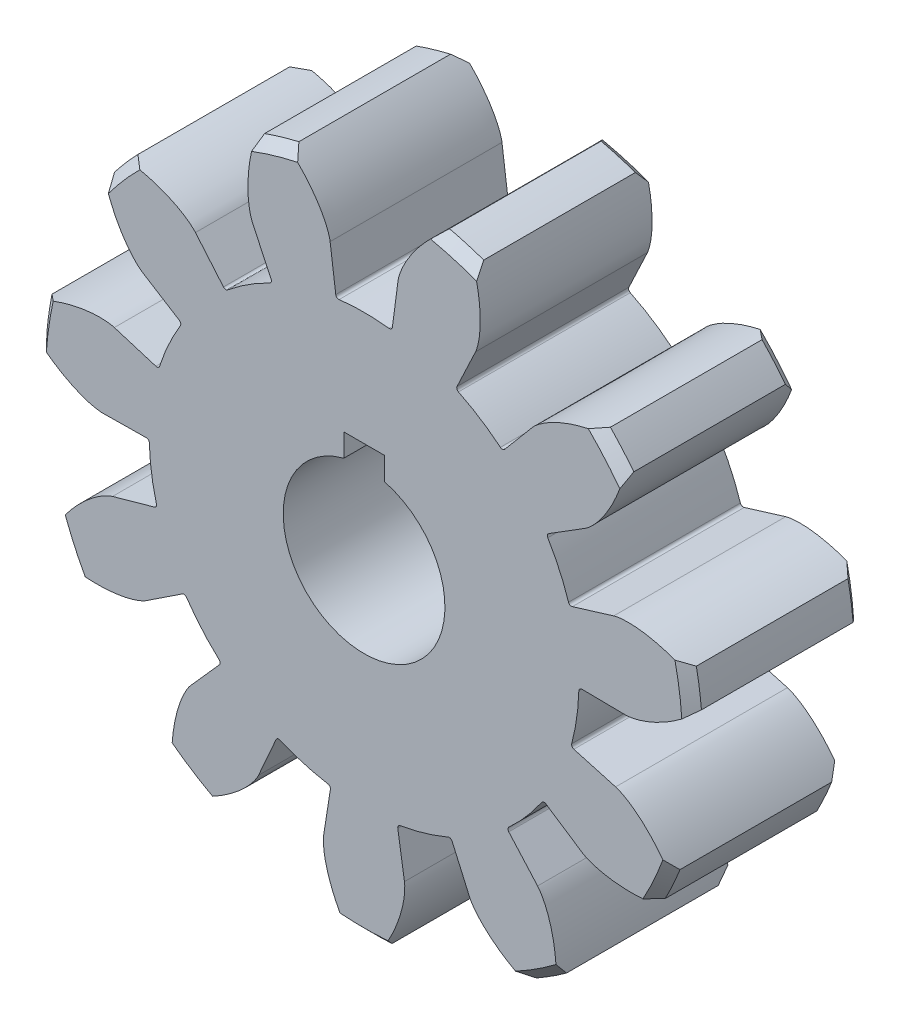
SolidWorks part; units mm, degrees
material "45钢"
ref_plane "中间平面" through (0, 0, 0) normal (0, 0, 1) x (1, 0, 0)
ref_plane "上视基准面" through (0, 0, 0) normal (0, 1, 0) x (1, 0, 0)
ref_plane "右视基准面" through (0, 0, 0) normal (1, 0, 0) x (0, 0, -1)
sketch "直齿轮" plane through (0, 0, 0) normal (0, 0, 1) x (1, 0, 0)
  line L0 (0, 0) -> (-3.9137, 27.2201) construction
  line L2 (-3.3586, 25.6224) -> (0, 0)
  line L3 (0, 0) -> (0, 52) construction
  line L4 (3.9137, 27.2201) -> (0, 0) construction
  line L6 (0, 0) -> (3.3586, 25.6224)
  circle A0 centre (0, 0) radius 25.8415
  circle A1 centre (0, 0) radius 21.25
  arc A2 (3.9137, 27.2201) -> (-3.9137, 27.2201) centre (0, 0) ccw
  circle A3 centre (0, 0) radius 32.5
  spline S0 degree 4 poles (-3.3586, 25.6224) (-3.365, 25.6711) (-3.3808, 25.7681) (-3.4242, 25.9599) (-3.5041, 26.2339) (-3.6124, 26.5402) (-3.785, 26.9591) (-3.9928, 27.3917) (-4.2404, 27.8444) (-4.5946, 28.4213) (-5.2533, 29.3745) (-6.3772, 30.7008) (-8.2958, 32.4638) (-11.0714, 34.3349) (-14.384, 35.9311) (-18.1561, 37.1417) (-22.0468, 37.8764) (-25.9943, 38.1671) (-30.145, 38.0374) (-35.2405, 37.342) (-41.1698, 35.739) (-47.716, 32.8899) (-53.574, 29.1708) (-58.168, 25.4106) (-62.3937, 21.2502) (-65.5961, 17.4804) (-68.4649, 13.4522) (-70.9915, 9.2061) (-72.805, 5.694) (-74.8101, 1.1783) (-76.7959, -4.4124) (-78.4995, -11.1266) (-79.406, -17.4933) (-79.7217, -22.4252) (-79.7681, -25.8813) (-79.7478, -27.6111) (-79.7001, -29.0886) (-79.6435, -30.2394) (-79.5962, -31.0377) (-79.5441, -31.7819) (-79.4996, -32.3689) (-79.433, -33.143) (-79.3812, -33.6954) (-79.2898, -34.5985) (-79.2094, -35.2953) (-79.1072, -36.1434) (-79.0057, -36.8995) (-78.8916, -37.7083) (-78.7726, -38.4857) (-78.6128, -39.4748) (-78.4068, -40.6487) (-78.144, -42.0214) (-77.8557, -43.3842) (-77.5899, -44.5511) (-77.4032, -45.3251) (-77.3073, -45.7124) (-77.2588, -45.9055) knots 0 0 0 0 0 0.001401 0.002802 0.005604 0.008133 0.010661 0.015718 0.019279 0.022839 0.02996 0.048734 0.068727 0.096889 0.125051 0.153212 0.181374 0.209535 0.237696 0.271429 0.327752 0.384075 0.440398 0.46856 0.496721 0.553044 0.581206 0.609367 0.637529 0.66569 0.722013 0.778336 0.834659 0.84874 0.86282 0.876901 0.883942 0.890982 0.895509 0.900036 0.904564 0.909091 0.914773 0.920455 0.926136 0.931818 0.9375 0.943182 0.948864 0.954545 0.965909 0.977273 0.988636 0.994318 1 1 1 1 1 construction
  spline S1 degree 4 poles (-3.3586, 25.6224) (-3.365, 25.6711) (-3.3808, 25.7681) (-3.4242, 25.9599) (-3.5041, 26.2339) (-3.6124, 26.5402) (-3.785, 26.9591) (-3.9928, 27.3917) (-4.2404, 27.8444) (-4.5946, 28.4213) (-5.2533, 29.3745) (-6.3772, 30.7008) (-8.2958, 32.4638) (-11.0714, 34.3349) (-14.384, 35.9311) (-18.1561, 37.1417) (-22.0468, 37.8764) (-25.9943, 38.1671) (-30.145, 38.0374) (-35.2405, 37.342) (-41.1698, 35.739) (-47.716, 32.8899) (-53.574, 29.1708) (-58.168, 25.4106) (-62.3937, 21.2502) (-65.5961, 17.4804) (-68.4649, 13.4522) (-70.9915, 9.2061) (-72.805, 5.694) (-74.8101, 1.1783) (-76.7959, -4.4124) (-78.4995, -11.1266) (-79.406, -17.4933) (-79.7217, -22.4252) (-79.7681, -25.8813) (-79.7478, -27.6111) (-79.7001, -29.0886) (-79.6435, -30.2394) (-79.5962, -31.0377) (-79.5441, -31.7819) (-79.4996, -32.3689) (-79.4526, -32.9146) (-79.4264, -33.2055) (-79.4131, -33.3492) knots 0 0 0 0 0 0.001401 0.002802 0.005604 0.008133 0.010661 0.015718 0.019279 0.022839 0.02996 0.048734 0.068727 0.096889 0.125051 0.153212 0.181374 0.209535 0.237696 0.271429 0.327752 0.384075 0.440398 0.46856 0.496721 0.553044 0.581206 0.609367 0.637529 0.66569 0.722013 0.778336 0.834659 0.84874 0.86282 0.876901 0.883942 0.890982 0.895509 0.900036 0.904564 0.909091 0.909091 0.909091 0.909091 0.909091
  spline S2 degree 4 poles (3.3586, 25.6224) (3.365, 25.6711) (3.3808, 25.7681) (3.4242, 25.9599) (3.5041, 26.2339) (3.6124, 26.5402) (3.785, 26.9591) (3.9928, 27.3917) (4.2404, 27.8444) (4.5946, 28.4213) (5.2533, 29.3745) (6.3772, 30.7008) (8.2958, 32.4638) (11.0714, 34.3349) (14.384, 35.9311) (18.1561, 37.1417) (22.0468, 37.8764) (25.9943, 38.1671) (30.145, 38.0374) (35.2405, 37.342) (41.1698, 35.739) (47.716, 32.8899) (53.574, 29.1708) (58.168, 25.4106) (62.3937, 21.2502) (65.5961, 17.4804) (68.4649, 13.4522) (70.9915, 9.2061) (72.805, 5.694) (74.8101, 1.1783) (76.7959, -4.4124) (78.4995, -11.1266) (79.406, -17.4933) (79.7217, -22.4252) (79.7681, -25.8813) (79.7478, -27.6111) (79.7001, -29.0886) (79.6435, -30.2394) (79.5962, -31.0377) (79.5441, -31.7819) (79.4996, -32.3689) (79.433, -33.143) (79.3812, -33.6954) (79.2898, -34.5985) (79.2094, -35.2953) (79.1072, -36.1434) (79.0057, -36.8995) (78.8916, -37.7083) (78.7726, -38.4857) (78.6128, -39.4748) (78.4068, -40.6487) (78.144, -42.0214) (77.8557, -43.3842) (77.5899, -44.5511) (77.4032, -45.3251) (77.3073, -45.7124) (77.2588, -45.9055) knots 0 0 0 0 0 0.001401 0.002802 0.005604 0.008133 0.010661 0.015718 0.019279 0.022839 0.02996 0.048734 0.068727 0.096889 0.125051 0.153212 0.181374 0.209535 0.237696 0.271429 0.327752 0.384075 0.440398 0.46856 0.496721 0.553044 0.581206 0.609367 0.637529 0.66569 0.722013 0.778336 0.834659 0.84874 0.86282 0.876901 0.883942 0.890982 0.895509 0.900036 0.904564 0.909091 0.914773 0.920455 0.926136 0.931818 0.9375 0.943182 0.948864 0.954545 0.965909 0.977273 0.988636 0.994318 1 1 1 1 1 construction
  spline S3 degree 4 poles (3.3586, 25.6224) (3.365, 25.6711) (3.3808, 25.7681) (3.4242, 25.9599) (3.5041, 26.2339) (3.6124, 26.5402) (3.785, 26.9591) (3.9928, 27.3917) (4.2404, 27.8444) (4.5946, 28.4213) (5.2533, 29.3745) (6.3772, 30.7008) (8.2958, 32.4638) (11.0714, 34.3349) (14.384, 35.9311) (18.1561, 37.1417) (22.0468, 37.8764) (25.9943, 38.1671) (30.145, 38.0374) (35.2405, 37.342) (41.1698, 35.739) (47.716, 32.8899) (53.574, 29.1708) (58.168, 25.4106) (62.3937, 21.2502) (65.5961, 17.4804) (68.4649, 13.4522) (70.9915, 9.2061) (72.805, 5.694) (74.8101, 1.1783) (76.7959, -4.4124) (78.4995, -11.1266) (79.406, -17.4933) (79.7217, -22.4252) (79.7681, -25.8813) (79.7478, -27.6111) (79.7001, -29.0886) (79.6435, -30.2394) (79.5962, -31.0377) (79.5441, -31.7819) (79.4996, -32.3689) (79.4526, -32.9146) (79.4264, -33.2055) (79.4131, -33.3492) knots 0 0 0 0 0 0.001401 0.002802 0.005604 0.008133 0.010661 0.015718 0.019279 0.022839 0.02996 0.048734 0.068727 0.096889 0.125051 0.153212 0.181374 0.209535 0.237696 0.271429 0.327752 0.384075 0.440398 0.46856 0.496721 0.553044 0.581206 0.609367 0.637529 0.66569 0.722013 0.778336 0.834659 0.84874 0.86282 0.876901 0.883942 0.890982 0.895509 0.900036 0.904564 0.909091 0.909091 0.909091 0.909091 0.909091
  dimension "基圆直径" = 51.6831
  dimension "齿根圆" = 42.5
  dimension "分度圆" = 55
  dimension "齿顶圆" = 65
  dimension "D1" = 7.854
sketch "圆" plane through (0, 0, 0) normal (0, 0, 1) x (1, 0, 0)
  circle A0 centre (0, 0) radius 32.5 construction
  circle A1 centre (0, 0) radius 32.5
extrude "毛胚" add sketch "圆" along normal mid plane 17
chamfer "轮齿倒角" distance 1 angle 45 2 edges at (32.5, 0, -8.5) (32.5, 0, 8.5)
sketch "齿形" plane through (0, 0, 0) normal (0, 0, 1) x (1, 0, 0)
  line L4 (0, 0) -> (3.3586, 25.6224) construction
  line L5 (-3.3586, 25.6224) -> (0, 0) construction
  line L6 (0, 0) -> (3.3586, 25.6224)
  line L7 (-3.3586, 25.6224) -> (0, 0)
  circle A4 centre (0, 0) radius 21.25 construction
  circle A5 centre (0, 0) radius 32.5 construction
  circle A6 centre (0, 0) radius 21.25
  circle A7 centre (0, 0) radius 32.5
  spline S1 degree 4 poles (-992.9335, 109.716) (35.3415, 16.0413) (3.7088, 21.5381) (2.8628, 24.0362) (3.5041, 26.2339) (3.6124, 26.5402) (3.785, 26.9591) (3.9928, 27.3917) (4.2404, 27.8444) (4.5946, 28.4213) (5.2533, 29.3745) (6.3772, 30.7008) (8.2958, 32.4638) (11.0714, 34.3349) (14.384, 35.9311) (18.1561, 37.1417) (22.0468, 37.8764) (25.9943, 38.1671) (30.145, 38.0374) (35.2405, 37.342) (41.1698, 35.739) (47.716, 32.8899) (53.574, 29.1708) (58.168, 25.4106) (62.3937, 21.2502) (65.5961, 17.4804) (68.4649, 13.4522) (70.9915, 9.2061) (72.805, 5.694) (74.8101, 1.1783) (76.7959, -4.4124) (78.4995, -11.1266) (79.406, -17.4933) (79.7217, -22.4252) (79.7681, -25.8813) (79.7478, -27.6111) (79.7001, -29.0886) (79.6435, -30.2394) (79.5962, -31.0377) (79.5441, -31.7819) (79.3569, -34.2494) (78.8042, -39.5007) (82.4838, 1.7263) (-13.4885, -1028.9483) knots -0.057112 -0.057112 -0.057112 -0.057112 -0.057112 0.001401 0.002802 0.005604 0.008133 0.010661 0.015718 0.019279 0.022839 0.02996 0.048734 0.068727 0.096889 0.125051 0.153212 0.181374 0.209535 0.237696 0.271429 0.327752 0.384075 0.440398 0.46856 0.496721 0.553044 0.581206 0.609367 0.637529 0.66569 0.722013 0.778336 0.834659 0.84874 0.86282 0.876901 0.883942 0.890982 0.895509 0.900036 0.904564 0.967102 0.967102 0.967102 0.967102 0.967102 only from (3.3586, 25.6224) to (79.4131, -33.3492) construction
  spline S3 degree 4 poles (992.9335, 109.716) (-35.3415, 16.0413) (-3.7088, 21.5381) (-2.8628, 24.0362) (-3.5041, 26.2339) (-3.6124, 26.5402) (-3.785, 26.9591) (-3.9928, 27.3917) (-4.2404, 27.8444) (-4.5946, 28.4213) (-5.2533, 29.3745) (-6.3772, 30.7008) (-8.2958, 32.4638) (-11.0714, 34.3349) (-14.384, 35.9311) (-18.1561, 37.1417) (-22.0468, 37.8764) (-25.9943, 38.1671) (-30.145, 38.0374) (-35.2405, 37.342) (-41.1698, 35.739) (-47.716, 32.8899) (-53.574, 29.1708) (-58.168, 25.4106) (-62.3937, 21.2502) (-65.5961, 17.4804) (-68.4649, 13.4522) (-70.9915, 9.2061) (-72.805, 5.694) (-74.8101, 1.1783) (-76.7959, -4.4124) (-78.4995, -11.1266) (-79.406, -17.4933) (-79.7217, -22.4252) (-79.7681, -25.8813) (-79.7478, -27.6111) (-79.7001, -29.0886) (-79.6435, -30.2394) (-79.5962, -31.0377) (-79.5441, -31.7819) (-79.3569, -34.2494) (-78.8042, -39.5007) (-82.4838, 1.7263) (13.4885, -1028.9483) knots -0.057112 -0.057112 -0.057112 -0.057112 -0.057112 0.001401 0.002802 0.005604 0.008133 0.010661 0.015718 0.019279 0.022839 0.02996 0.048734 0.068727 0.096889 0.125051 0.153212 0.181374 0.209535 0.237696 0.271429 0.327752 0.384075 0.440398 0.46856 0.496721 0.553044 0.581206 0.609367 0.637529 0.66569 0.722013 0.778336 0.834659 0.84874 0.86282 0.876901 0.883942 0.890982 0.895509 0.900036 0.904564 0.967102 0.967102 0.967102 0.967102 0.967102 only from (-3.3586, 25.6224) to (-79.4131, -33.3492) construction
  spline S4 degree 4 poles (3.3586, 25.6224) (3.365, 25.6711) (3.3808, 25.7681) (3.4242, 25.9599) (3.5041, 26.2339) (3.6124, 26.5402) (3.785, 26.9591) (3.9928, 27.3917) (4.2404, 27.8444) (4.5946, 28.4213) (5.2533, 29.3745) (6.3772, 30.7008) (8.2958, 32.4638) (11.0714, 34.3349) (14.384, 35.9311) (18.1561, 37.1417) (22.0468, 37.8764) (25.9943, 38.1671) (30.145, 38.0374) (35.2405, 37.342) (41.1698, 35.739) (47.716, 32.8899) (53.574, 29.1708) (58.168, 25.4106) (62.3937, 21.2502) (65.5961, 17.4804) (68.4649, 13.4522) (70.9915, 9.2061) (72.805, 5.694) (74.8101, 1.1783) (76.7959, -4.4124) (78.4995, -11.1266) (79.406, -17.4933) (79.7217, -22.4252) (79.7681, -25.8813) (79.7478, -27.6111) (79.7001, -29.0886) (79.6435, -30.2394) (79.5962, -31.0377) (79.5441, -31.7819) (79.4996, -32.3689) (79.4526, -32.9146) (79.4264, -33.2055) (79.4131, -33.3492) knots 0 0 0 0 0 0.001401 0.002802 0.005604 0.008133 0.010661 0.015718 0.019279 0.022839 0.02996 0.048734 0.068727 0.096889 0.125051 0.153212 0.181374 0.209535 0.237696 0.271429 0.327752 0.384075 0.440398 0.46856 0.496721 0.553044 0.581206 0.609367 0.637529 0.66569 0.722013 0.778336 0.834659 0.84874 0.86282 0.876901 0.883942 0.890982 0.895509 0.900036 0.904564 0.909091 0.909091 0.909091 0.909091 0.909091
  spline S5 degree 4 poles (-3.3586, 25.6224) (-3.365, 25.6711) (-3.3808, 25.7681) (-3.4242, 25.9599) (-3.5041, 26.2339) (-3.6124, 26.5402) (-3.785, 26.9591) (-3.9928, 27.3917) (-4.2404, 27.8444) (-4.5946, 28.4213) (-5.2533, 29.3745) (-6.3772, 30.7008) (-8.2958, 32.4638) (-11.0714, 34.3349) (-14.384, 35.9311) (-18.1561, 37.1417) (-22.0468, 37.8764) (-25.9943, 38.1671) (-30.145, 38.0374) (-35.2405, 37.342) (-41.1698, 35.739) (-47.716, 32.8899) (-53.574, 29.1708) (-58.168, 25.4106) (-62.3937, 21.2502) (-65.5961, 17.4804) (-68.4649, 13.4522) (-70.9915, 9.2061) (-72.805, 5.694) (-74.8101, 1.1783) (-76.7959, -4.4124) (-78.4995, -11.1266) (-79.406, -17.4933) (-79.7217, -22.4252) (-79.7681, -25.8813) (-79.7478, -27.6111) (-79.7001, -29.0886) (-79.6435, -30.2394) (-79.5962, -31.0377) (-79.5441, -31.7819) (-79.4996, -32.3689) (-79.4526, -32.9146) (-79.4264, -33.2055) (-79.4131, -33.3492) knots 0 0 0 0 0 0.001401 0.002802 0.005604 0.008133 0.010661 0.015718 0.019279 0.022839 0.02996 0.048734 0.068727 0.096889 0.125051 0.153212 0.181374 0.209535 0.237696 0.271429 0.327752 0.384075 0.440398 0.46856 0.496721 0.553044 0.581206 0.609367 0.637529 0.66569 0.722013 0.778336 0.834659 0.84874 0.86282 0.876901 0.883942 0.890982 0.895509 0.900036 0.904564 0.909091 0.909091 0.909091 0.909091 0.909091
extrude "插齿" cut sketch "齿形" against normal mid plane 17 contours S5 A6 S4 A7
fillet "圆角1" [suppressed] radius 0.3
pattern_circular "圆周阵列1" [suppressed] count 11 over 360
fillet "圆角2" radius 0.3 2 edges at (2.7619, 21.0698, 0) (-2.7619, 21.0698, 0)
pattern_circular "圆周阵列2" count 11 over 360 about axis through (0, 0, 8.5) along (0, 0, -1) of "圆角2", "插齿"
sketch "分度圆" plane through (0, 0, 0) normal (0, 0, 1) x (1, 0, 0)
  circle A0 centre (0, 0) radius 27.5 construction
  circle A1 centre (0, 0) radius 27.5 construction
sketch "草图1" plane through (0, 0, 8.5) normal (0, 0, 1) x (1, 0, 0)
  line L1 (-2, 10) -> (2, 10)
  line L2 (-2, 10) -> (-2, 6)
  line L3 (-2, 6) -> (2, 6)
  line L4 (2, 10) -> (2, 6)
  line L5 (-2, 10) -> (2, 6) construction
  line L6 (-2, 6) -> (2, 10) construction
  circle A0 centre (0, 0) radius 8
  point P3 (0, 8)
  dimension "D1" = 16
  dimension "D2" = 4
  dimension "D3" = 18
extrude "切除-拉伸2" cut sketch "草图1" against normal through all contours L2 A0 L4 L3 | L4 A0 L2 L3 | A0 L4 L1 L2
equation "\"m\" = 5'模数"
equation "\"z\"= 11'齿数"
equation "\"a\"= 20'压力角（常见为20°）"
equation "\"B\"= 17'齿宽"
equation "\"C1\"= 1'轮齿倒角（若设为0，则无倒角）"
equation "\"x\"= 0'变位系数（不懂勿动）"
equation "\"ha\"= 1'齿顶高系数（不懂勿动）"
equation "\"c\"= 0.25'顶隙系数（不懂勿动）"
equation "\"基圆直径@直齿轮\"= \"m\" * \"z\" * cos ( \"a\" )"
equation "\"齿根圆@直齿轮\" = \"m\" * ( \"z\" - 2 * ( \"ha\" - \"x\" + \"c\" ) )"
equation "\"分度圆@直齿轮\"=\"m\" * \"z\""
equation "\"齿顶圆@直齿轮\" = \"m\" * ( \"z\" + 2 * ( \"ha\" + \"x\" ) )"
equation "\"R\"= 0.3'齿根圆角"
equation "\"D1\"= \"R\""
equation "\"D1@毛胚\" = \"B\""
equation "\"D1@轮齿倒角\" = IIF ( \"C1\" > 0 , \"C1\" , 0.001 )"
equation "\"轮齿倒角\"= IIF ( \"C1\" > 0 , \"unsuppressed\" , \"suppressed\" )"
equation "\"D1@插齿\" = \"B\""
equation "\"D1@圆周阵列1\" = \"z\""
equation "\"D1@直齿轮\"= \"m\" * ( pi / 2 ) - 2 * \"m\" * tan ( \"a\" ) * \"x\"'作者：机械菌-"
equation "\"D1@圆角1\"=\"R\""
equation "\"圆角1\" = IIF ( \"m\" * ( \"z\" - 2 * ( \"ha\" - \"x\" + \"c\" ) ) > \"m\" * \"z\" * cos ( \"a\" ) , \"unsuppressed\" , \"suppressed\" )"
equation "\"圆周阵列1\"= IIF ( \"m\" * ( \"z\" - 2 * ( \"ha\" - \"x\" + \"c\" ) ) > \"m\" * \"z\" * cos ( \"a\" ) , \"unsuppressed\" , \"suppressed\" )"
equation "\"D1@圆角2\"=\"R\""
equation "\"D1@圆周阵列2\" = \"z\""
equation "\"圆角2\" = IIF ( \"m\" * ( \"z\" - 2 * ( \"ha\" - \"x\" + \"c\" ) ) < \"m\" * \"z\" * cos ( \"a\" ) , \"unsuppressed\" , \"suppressed\" )"
equation "\"圆周阵列2\"= IIF ( \"m\" *  ( \"z\" - 2 *  ( \"ha\" - \"x\" + \"c\" )  )  < \"m\" * \"z\" * cos ( \"a\" )  ,  unsuppressed  ,  suppressed  ) "
